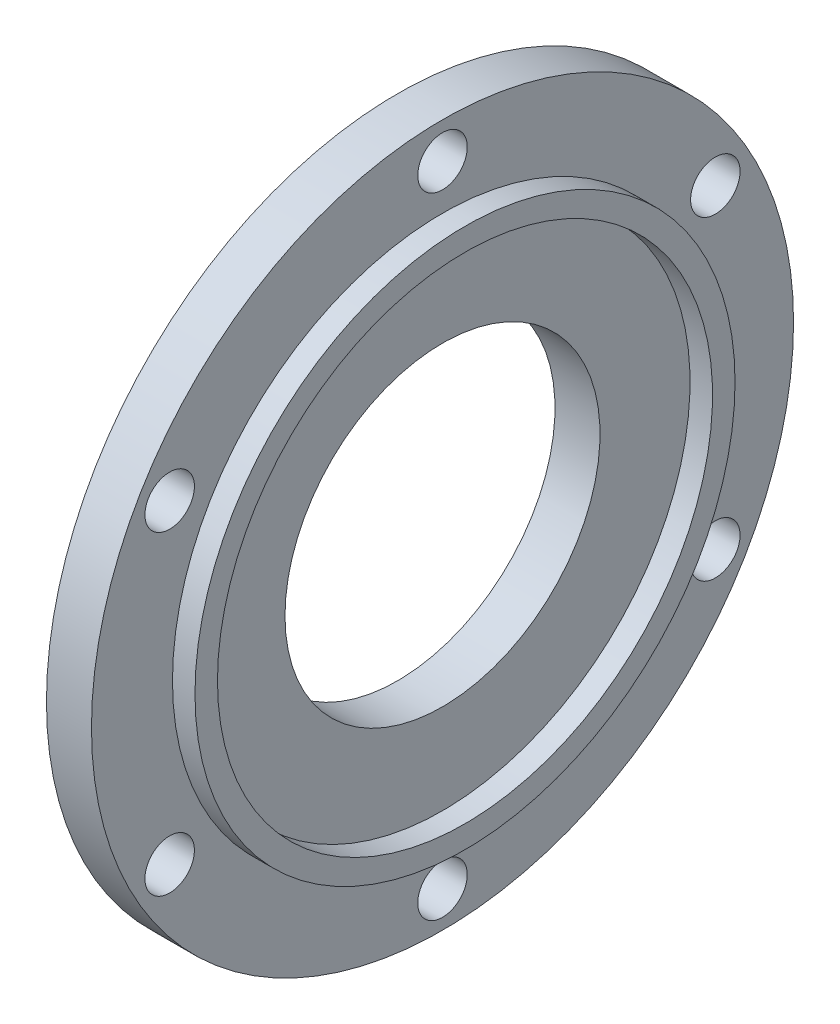
SolidWorks part; units mm, degrees
ref_plane "Front Plane" through (0, 0, 0) normal (0, 0, 1) x (1, 0, 0)
ref_plane "Top Plane" through (0, 0, 0) normal (0, 1, 0) x (1, 0, 0)
ref_plane "Right Plane" through (0, 0, 0) normal (1, 0, 0) x (0, 0, -1)
sketch "Sketch1" plane through (0, 0, 0) normal (0, 0, 1) x (1, 0, 0)
  line L0 (0, 78) -> (0, 35)
  line L1 (0, -55) -> (0, 55) construction
  line L2 (0, 35) -> (10, 35)
  line L3 (10, 35) -> (10, 55)
  line L4 (10, 55) -> (15, 55)
  line L5 (15, 55) -> (15, 60)
  line L6 (15, 60) -> (10, 60)
  line L7 (10, 60) -> (10, 78)
  line L8 (10, 78) -> (0, 78)
  line L9 (55, 0) -> (-55, 0) construction
  line L10 (0, 0) -> (44.7364, 0) construction
  dimension "D1" = 10
  dimension "D2" = 18
  dimension "D3" = 60
  dimension "D4" = 35
  dimension "D5" = 10
  dimension "D6" = 5
  dimension "D7" = 55
revolve "Revolve1" add sketch "Sketch1" angle 360 about L10
sketch "Sketch2" plane through (10, 0, 0) normal (1, 0, 0) x (0, 0, -1)
  line L0 (0, 0) -> (60.6218, 35) construction
  circle A0 centre (0, 0) radius 70
  circle A1 centre (60.6218, 35) radius 5.5
  dimension "D1" = 140
  dimension "D2" = 11
extrude "Cut-Extrude1" cut sketch "Sketch2" against normal blind 10 contours A1
pattern_circular "CirPattern1" count 6 over 360 about axis through (0, 0, 0) along (1, 0, 0) of "Cut-Extrude1"
